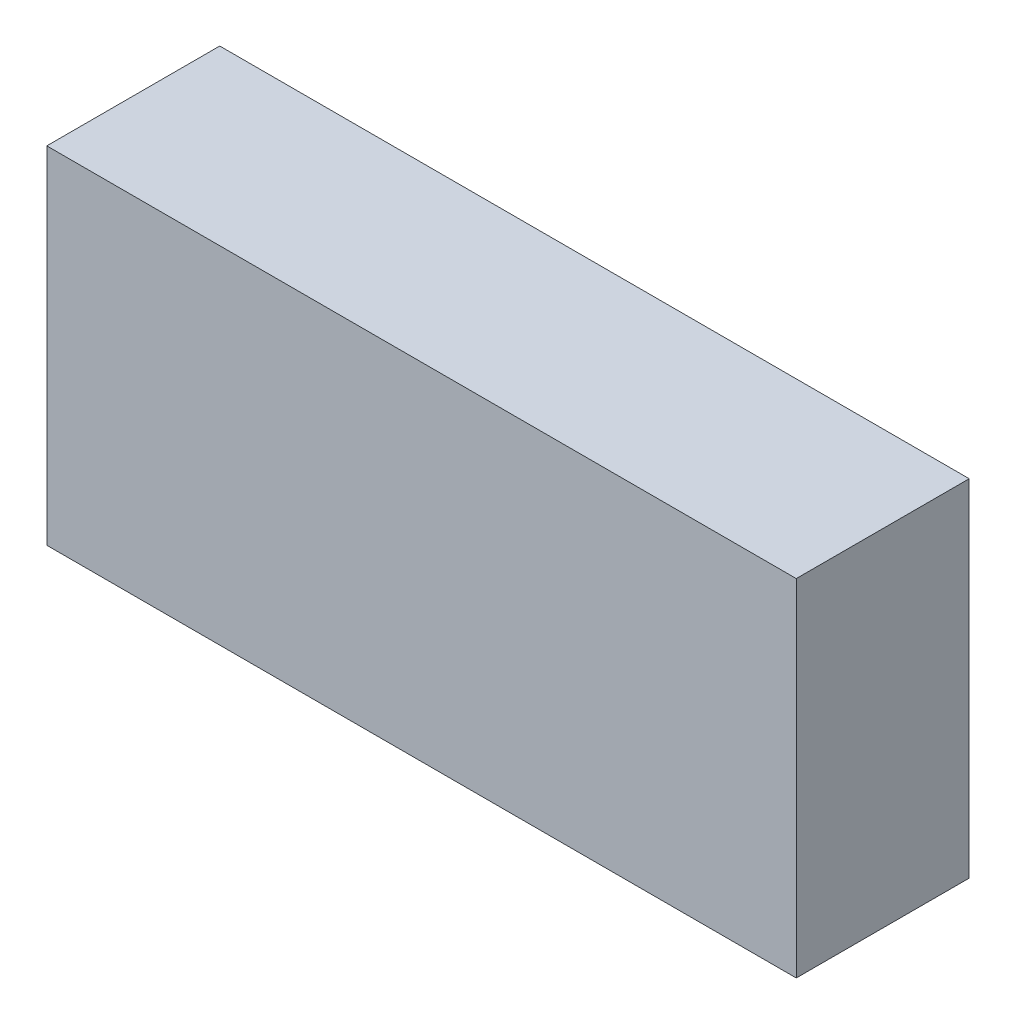
SolidWorks part; units mm, degrees
ref_plane "Front Plane" through (0, 0, 0) normal (0, 0, 1) x (1, 0, 0)
ref_plane "Top Plane" through (0, 0, 0) normal (0, 1, 0) x (1, 0, 0)
ref_plane "Right Plane" through (0, 0, 0) normal (1, 0, 0) x (0, 0, -1)
sketch "Sketch1" plane through (0, 0, 0) normal (0, 1, 0) x (1, 0, 0)
  line L1 (-41.275, -9.525) -> (41.275, -9.525)
  line L2 (-41.275, -9.525) -> (-41.275, 9.525)
  line L3 (-41.275, 9.525) -> (41.275, 9.525)
  line L4 (41.275, -9.525) -> (41.275, 9.525)
  line L5 (-41.275, -9.525) -> (41.275, 9.525) construction
  line L6 (-41.275, 9.525) -> (41.275, -9.525) construction
  point P0 (0, 0)
  dimension "D1" = 19.05
  dimension "D2" = 82.55
extrude "Boss-Extrude1" add sketch "Sketch1" along normal blind 38.1
sketch "Sketch2" [suppressed] plane through (0, 0, 9.525) normal (0, 0, 1) x (1, 0, 0)
  line L0 (0, 111.0644) -> (0, 0) construction
  circle A0 centre (0, 111.0644) radius 88.9
  dimension "D1" = 177.8
extrude "Cut-Extrude1" [suppressed] cut sketch "Sketch2" against normal through all
